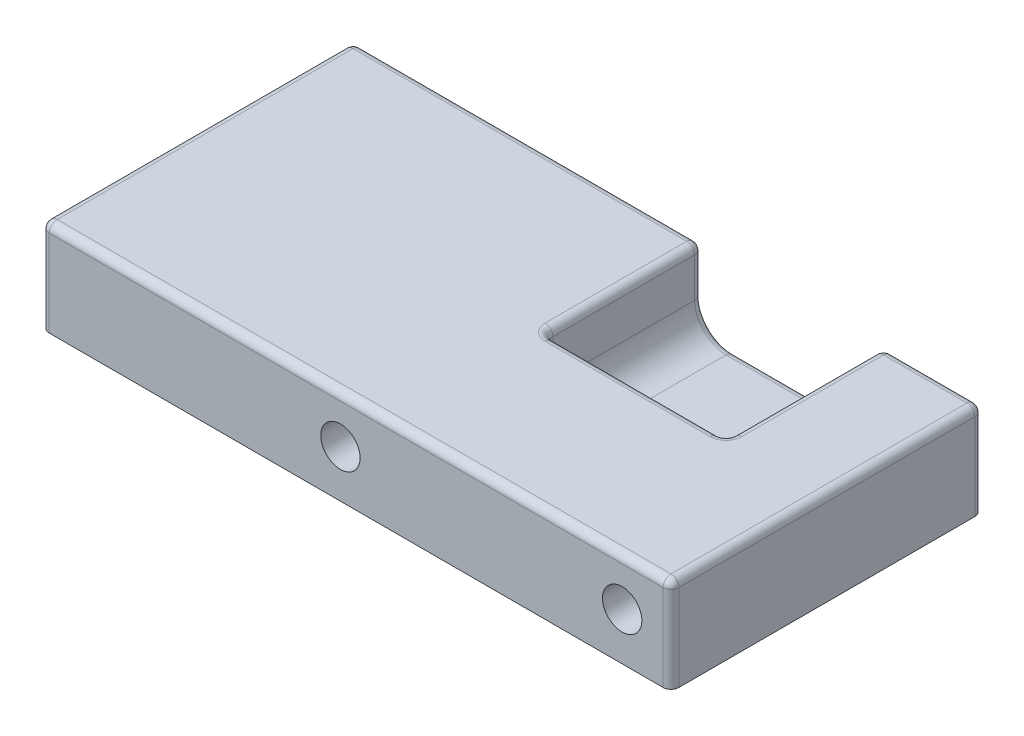
SolidWorks part; units mm, degrees
ref_plane "Front Plane" through (0, 0, 0) normal (0, 0, 1) x (1, 0, 0)
ref_plane "Top Plane" through (0, 0, 0) normal (0, 1, 0) x (1, 0, 0)
ref_plane "Right Plane" through (0, 0, 0) normal (1, 0, 0) x (0, 0, -1)
sketch "Sketch1" plane through (0, 0, 0) normal (0, 1, 0) x (1, 0, 0)
  line L1 (0, 0) -> (80, 0)
  line L2 (0, 0) -> (0, 39.6)
  line L3 (0, 39.6) -> (80, 39.6)
  line L4 (80, 0) -> (80, 39.6)
  dimension "D1" = 39.6
  dimension "D2" = 80
extrude "Boss-Extrude1" add sketch "Sketch1" along normal blind 12
sketch "Sketch2" plane through (0, 0, -39.6) normal (0, 0, -1) x (-1, 0, 0)
  line L0 (-80, 6) -> (0, 6) construction
  line L1 (-80, 12) -> (-80, 0) construction
  line L2 (0, 12) -> (0, 0) construction
  circle A0 centre (-38, 6) radius 2.5
  circle A1 centre (-73.8, 6) radius 2.5
  dimension "D1" = 5
  dimension "D2" = 35.8
  dimension "D3" = 38
extrude "Cut-Extrude2" cut sketch "Sketch2" against normal up to next
sketch "Sketch3" plane through (0, 0, -39.6) normal (0, 0, -1) x (-1, 0, 0)
  line L0 (-73.8, 6) -> (-38, 6) construction
  line L1 (-55.9, 12) -> (-55.9, 0) construction
  line L2 (-80, 12) -> (0, 12) construction
  line L3 (-80, 0) -> (0, 0) construction
  line L4 (-63.4, 2) -> (-48.4, 2)
  line L5 (-67.4, 6) -> (-67.4, 12)
  line L6 (-44.4, 6) -> (-44.4, 12)
  line L7 (-44.4, 12) -> (-67.4, 12)
  arc A0 (-67.4, 6) -> (-63.4, 2) centre (-63.4, 6) ccw
  arc A1 (-44.4, 6) -> (-48.4, 2) centre (-48.4, 6) cw
  point P10 (-55.9, 6)
  dimension "D1" = 8
  dimension "D2" = 15
extrude "Cut-Extrude3" cut sketch "Sketch3" against normal blind 20
fillet "Fillet1" radius 1 22 edges at (67.4, 12, -29.6) (67.4, 9, -19.6) (66.2284, 3.1716, -19.6) (55.9, 2, -19.6) (45.5716, 3.1716, -19.6) (67.4, 9, -39.6) (66.2284, 3.1716, -39.6) (55.9, 2, -39.6) (45.5716, 3.1716, -39.6) (44.4, 9, -19.6) (44.4, 12, -29.6) (44.4, 9, -39.6) (55.9, 12, -19.6) (0, 12, -19.8) (0, 6, 0) (40, 12, 0) (22.2, 12, -39.6) (0, 6, -39.6) (73.7, 12, -39.6) (80, 6, 0) (80, 12, -19.8) (80, 6, -39.6)
